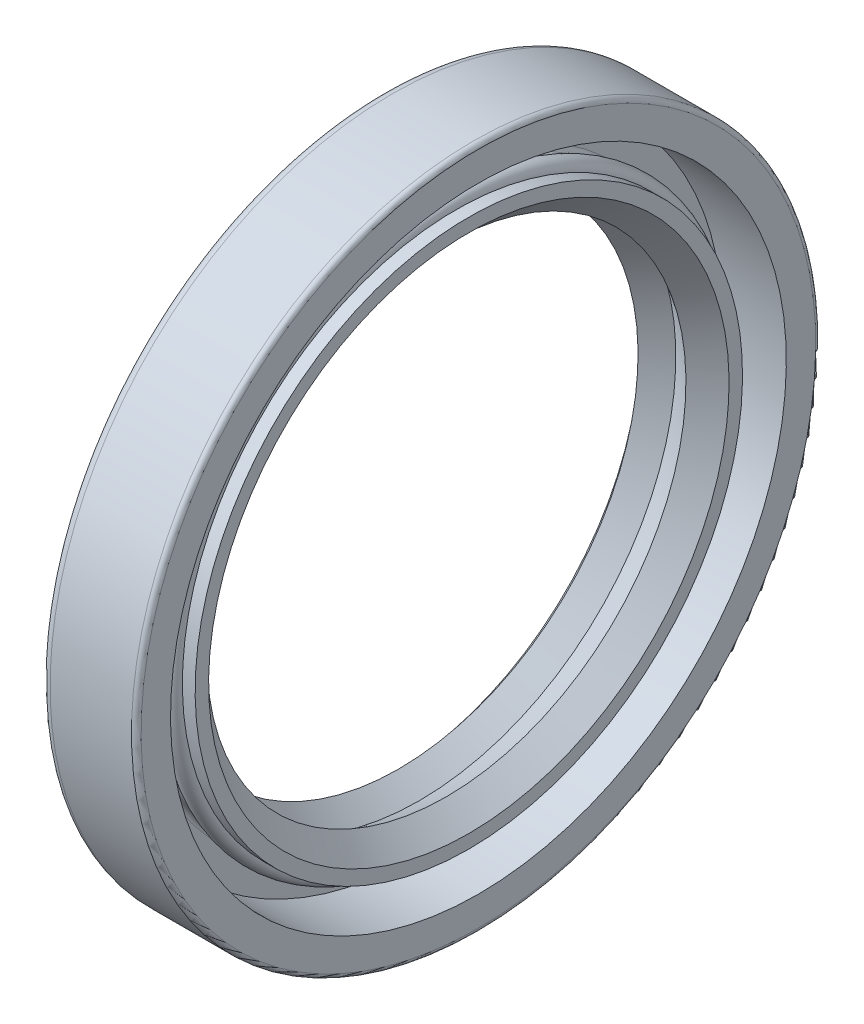
SolidWorks part; units mm, degrees
ref_plane "Front" through (0, 0, 0) normal (0, 0, 1) x (1, 0, 0)
ref_plane "Top" through (0, 0, 0) normal (0, 1, 0) x (1, 0, 0)
ref_plane "Right" through (0, 0, 0) normal (1, 0, 0) x (0, 0, -1)
sketch "Sketch1" plane through (0, 0, 0) normal (0, 0, 1) x (1, 0, 0)
  line L0 (0, 22.5) -> (0.2188, 22.5)
  line L1 (0.2188, 22.5) -> (0.2188, 20)
  line L2 (0.2188, 20) -> (0, 20)
  line L3 (0, 20) -> (0, 19.375)
  line L4 (0, 19.375) -> (1.1667, 18.75)
  line L5 (1.1667, 18.75) -> (0.5527, 18.242)
  line L6 (0.5527, 18.242) -> (1.1667, 17.5)
  line L7 (1.1667, 17.5) -> (2.6774, 18.75)
  line L8 (2.6774, 18.75) -> (4.6667, 17.5)
  line L9 (4.6667, 17.5) -> (6.3, 19.0167)
  line L10 (6.3, 19.0167) -> (6.3, 20)
  line L11 (6.3, 20) -> (5.3667, 20)
  line L12 (3.9667, 20) -> (2.6833, 20)
  line L13 (2.3333, 20.35) -> (2.3333, 22.5)
  line L14 (2.3333, 22.5) -> (7, 22.5)
  line L15 (7, 22.5) -> (7, 24.65)
  line L16 (6.65, 25) -> (0.7, 25)
  line L17 (0, 24.3) -> (0, 22.5)
  line L18 (7, 0) -> (0, 0) construction
  line L19 (1.1667, 17.5) -> (4.6667, 17.5) construction
  line L20 (3.675, 25) -> (3.675, 22.5) construction
  line L21 (3.675, 22.5) -> (3.675, 20) construction
  line L22 (3.675, 20) -> (3.675, 17.5) construction
  line L23 (4.6667, 20) -> (4.6667, 17.5) construction
  line L24 (0, 23.4) -> (2.3333, 23.4) construction
  line L25 (2.3333, 23.4) -> (4.6667, 23.4) construction
  line L26 (4.6667, 23.4) -> (7, 23.4) construction
  line L27 (4.6667, 20) -> (4.6667, 23.4) construction
  line L28 (2.3333, 20.35) -> (2.6774, 18.75) construction
  line L29 (3.675, 18.75) -> (2.6774, 18.75) construction
  line L30 (3.1762, 18.75) -> (3.1762, 20) construction
  line L31 (3.1762, 19.375) -> (0, 19.375) construction
  line L32 (2.6774, 18.75) -> (1.1667, 18.75) construction
  line L33 (1.1667, 17.5) -> (1.1667, 18.75) construction
  line L35 (7, 22.5) -> (7, 20) construction
  line L36 (7, 20) -> (6.3, 20) construction
  line L37 (0, 24.3) -> (0.7, 24.3) construction
  line L39 (1.1667, 23.4) -> (1.1667, 18.75) construction
  arc A0 (5.3667, 20) -> (3.9667, 20) centre (4.6667, 20) ccw construction
  arc A1 (2.6833, 20) -> (2.3333, 20.35) centre (2.6833, 20.35) cw
  arc A2 (7, 24.65) -> (6.65, 25) centre (6.65, 24.65) ccw
  arc A3 (0.7, 25) -> (0, 24.3) centre (0.7, 24.3) ccw
  arc A4 (3.9667, 20) -> (5.3667, 20) centre (4.6667, 20) ccw
  dimension "D3" = 0.7
  dimension "D4" = 0.35
  dimension "D2" = 0.2188
  dimension "D5" = 67.784
  dimension "D8" = 47.121
revolve "Revolve1" add sketch "Sketch1" angle 360 about L18
sketch "Sketch2" plane through (0, 0, 0) normal (0, 0, 1) x (1, 0, 0)
  line L0 (0, 0) -> (7, 0) construction
  circle A0 centre (4.6667, 20) radius 0.7
revolve "Revolve2" add sketch "Sketch2" angle 360 about L0
equation "\"D2@Sketch1\"=\"SealWidth@Sketch1\"*.03125"
equation "\"D3@Sketch1\"=\"SealWidth@Sketch1\"*.1"
equation "\"D4@Sketch1\"=\"D3@Sketch1\"*.5"
